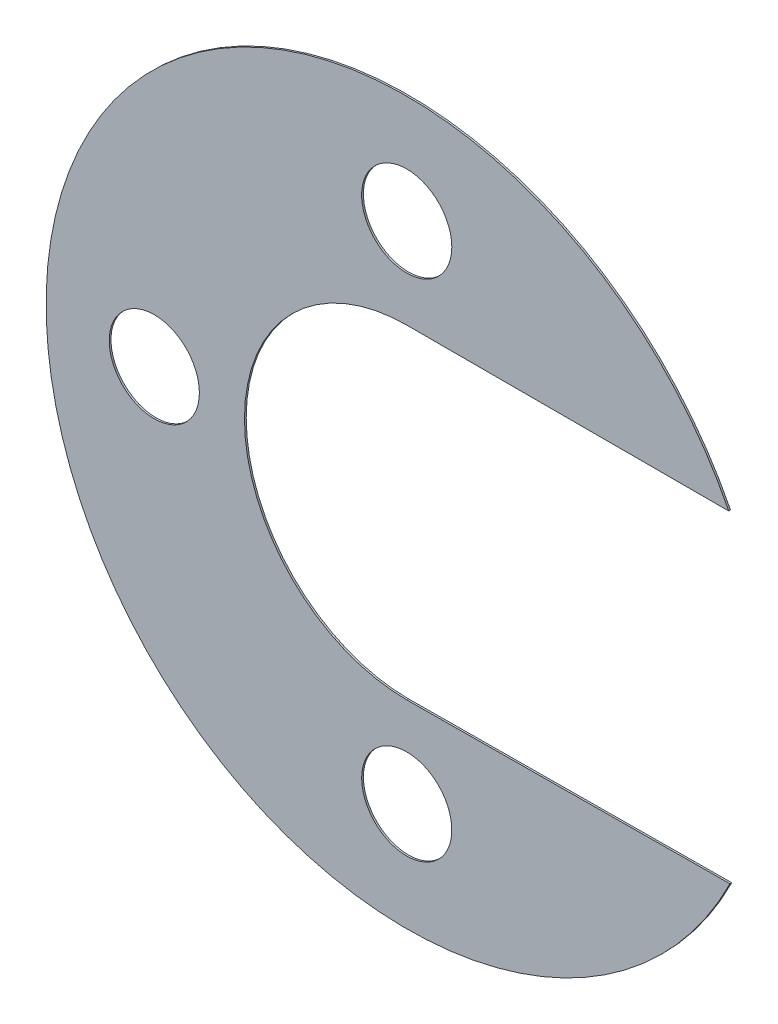
SolidWorks part; units mm, degrees
ref_plane "Front Plane" through (0, 0, 0) normal (0, 0, 1) x (1, 0, 0)
ref_plane "Top Plane" through (0, 0, 0) normal (0, 1, 0) x (1, 0, 0)
ref_plane "Right Plane" through (0, 0, 0) normal (1, 0, 0) x (0, 0, -1)
sketch "Sketch1" plane through (0, 0, 0) normal (0, 0, 1) x (1, 0, 0)
  line L0 (-3216.151, -1097.8705) -> (-380.4912, -1097.8705) construction
  line L1 (-2045.2885, 202.4021) -> (-2045.2885, -3053.8181) construction
  line L2 (-2449.9815, -1809.0705) -> (-1638.0084, -1809.0705) construction
  line L3 (-2449.9815, -386.6705) -> (-1638.0084, -386.6705) construction
  line L4 (-2045.2885, -640.6705) -> (-1137.9714, -640.6705)
  line L5 (-2756.4885, -780.2936) -> (-2756.4885, -1446.5279) construction
  line L6 (-1134.6177, -1548.3533) -> (-2045.2885, -1555.0705)
  arc A2 (-1137.9714, -640.6705) -> (-1134.6177, -1548.3533) centre (-2045.2885, -1097.8705) ccw
  circle A3 centre (-2045.2885, -386.6705) radius 127
  circle A4 centre (-2756.4885, -1097.8705) radius 127
  circle A5 centre (-2045.2885, -1809.0705) radius 127
  arc A6 (-2045.2885, -640.6705) -> (-2045.2885, -1555.0705) centre (-2045.2885, -1097.8705) ccw
  point P1 (0, 0)
  point P20 (0, 0)
  point P23 (0, 0)
extrude "Boss-Extrude1" add sketch "Sketch1" along normal blind 5
